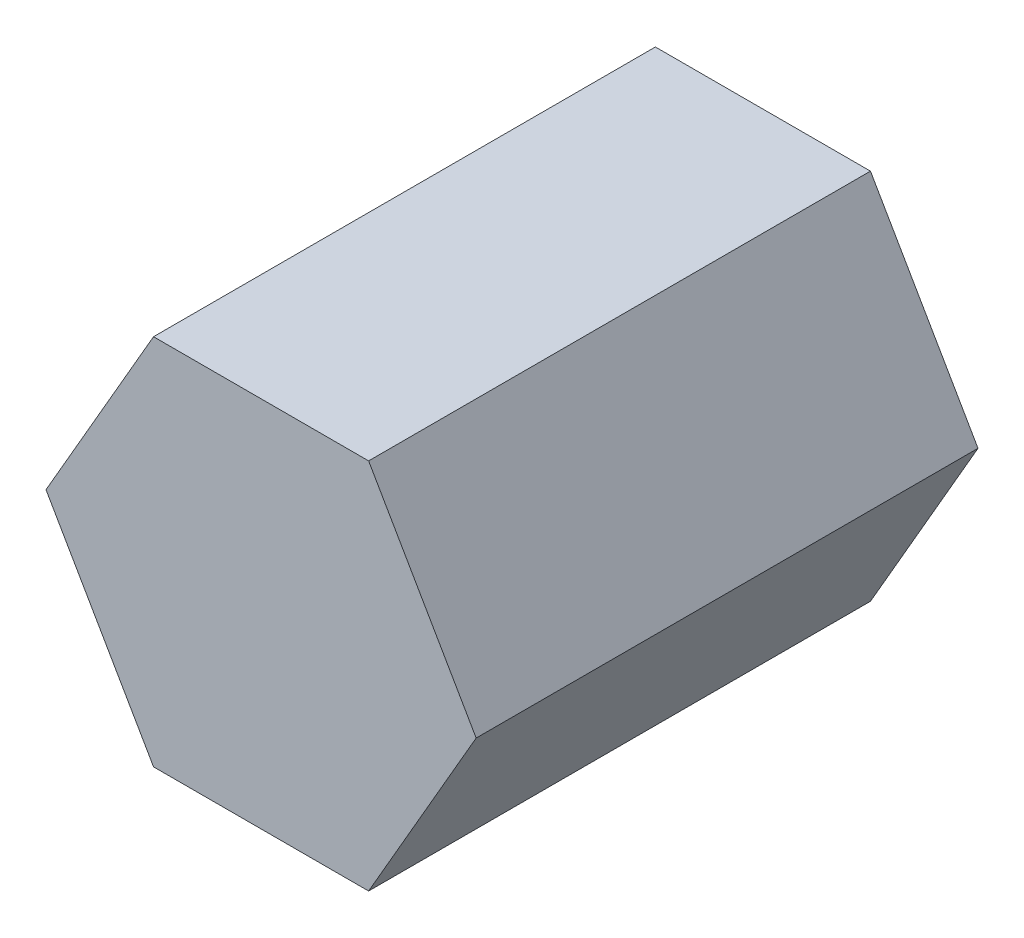
SolidWorks part; units mm, degrees
material "ABS"
ref_plane "Front Plane" through (0, 0, 0) normal (0, 0, 1) x (1, 0, 0)
ref_plane "Top Plane" through (0, 0, 0) normal (0, 1, 0) x (1, 0, 0)
ref_plane "Right Plane" through (0, 0, 0) normal (1, 0, 0) x (0, 0, -1)
sketch "Sketch1" plane through (0, 0, 0) normal (0, 0, 1) x (1, 0, 0)
  line L1 (1.5, -2.5981) -> (3, 0)
  line L2 (3, 0) -> (1.5, 2.5981)
  line L3 (1.5, 2.5981) -> (-1.5, 2.5981)
  line L4 (-1.5, 2.5981) -> (-3, 0)
  line L5 (-3, 0) -> (-1.5, -2.5981)
  line L6 (-1.5, -2.5981) -> (1.5, -2.5981)
  circle A0 centre (0, 0) radius 2.5981 construction
  point P1 (0, 0)
  dimension "D1" = 6
extrude "Boss-Extrude1" add sketch "Sketch1" along normal blind 7
